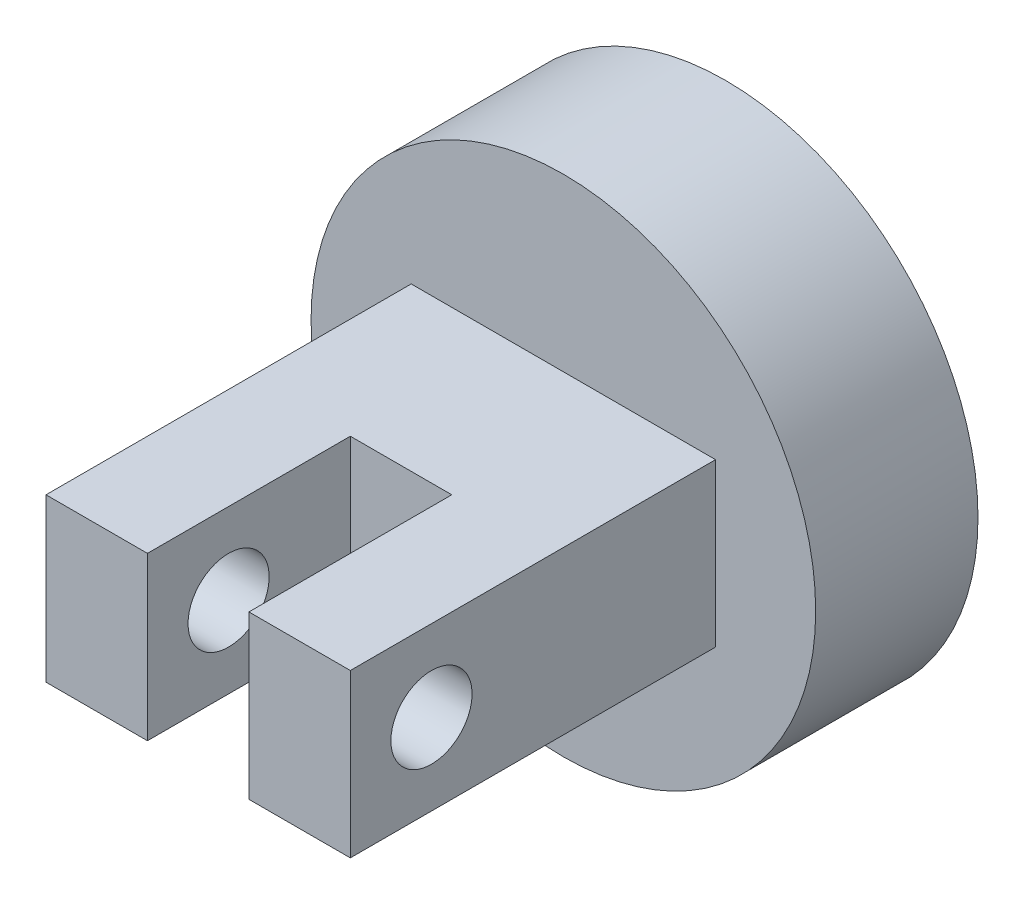
SolidWorks part; units mm, degrees
ref_plane "Front Plane" through (0, 0, 0) normal (0, 0, 1) x (1, 0, 0)
ref_plane "Top Plane" through (0, 0, 0) normal (0, 1, 0) x (1, 0, 0)
ref_plane "Right Plane" through (0, 0, 0) normal (1, 0, 0) x (0, 0, -1)
sketch "Sketch3" plane through (0, 0, 0) normal (0, 0, 1) x (1, 0, 0)
  circle A0 centre (0, 0) radius 124.3605
extrude "Boss-Extrude2" add sketch "Sketch3" along normal blind 80
sketch "Sketch4" plane through (0, 0, 0) normal (0, 0, 1) x (1, 0, 0)
  line L1 (-75, -40) -> (75, -40)
  line L2 (-75, -40) -> (-75, 40)
  line L3 (-75, 40) -> (75, 40)
  line L4 (75, -40) -> (75, 40)
  line L5 (-75, -40) -> (75, 40) construction
  line L6 (-75, 40) -> (75, -40) construction
  point P0 (0, 0)
  dimension "D1" = 150
  dimension "D2" = 80
extrude "Boss-Extrude4" add sketch "Sketch4" along normal blind 260
sketch "Sketch5" plane through (-75, 0, 0) normal (-1, 0, 0) x (0, 0, 1)
  circle A0 centre (220, 0) radius 20
extrude "Cut-Extrude1" cut sketch "Sketch5" against normal blind 260
sketch "Sketch6" plane through (0, 40, 0) normal (0, 1, 0) x (1, 0, 0)
  line L0 (75, -260) -> (-75, -260) construction
  line L1 (-25, -260) -> (25, -260)
  line L2 (-25, -260) -> (-25, -160)
  line L3 (-25, -160) -> (25, -160)
  line L4 (25, -260) -> (25, -160)
  line L5 (-75, -260) -> (-75, -80) construction
  line L6 (75, -260) -> (75, -80) construction
  dimension "D1" = 50
  dimension "D2" = 100
  dimension "D3" = 50
  dimension "D4" = 50
extrude "Cut-Extrude2" cut sketch "Sketch6" against normal blind 260
